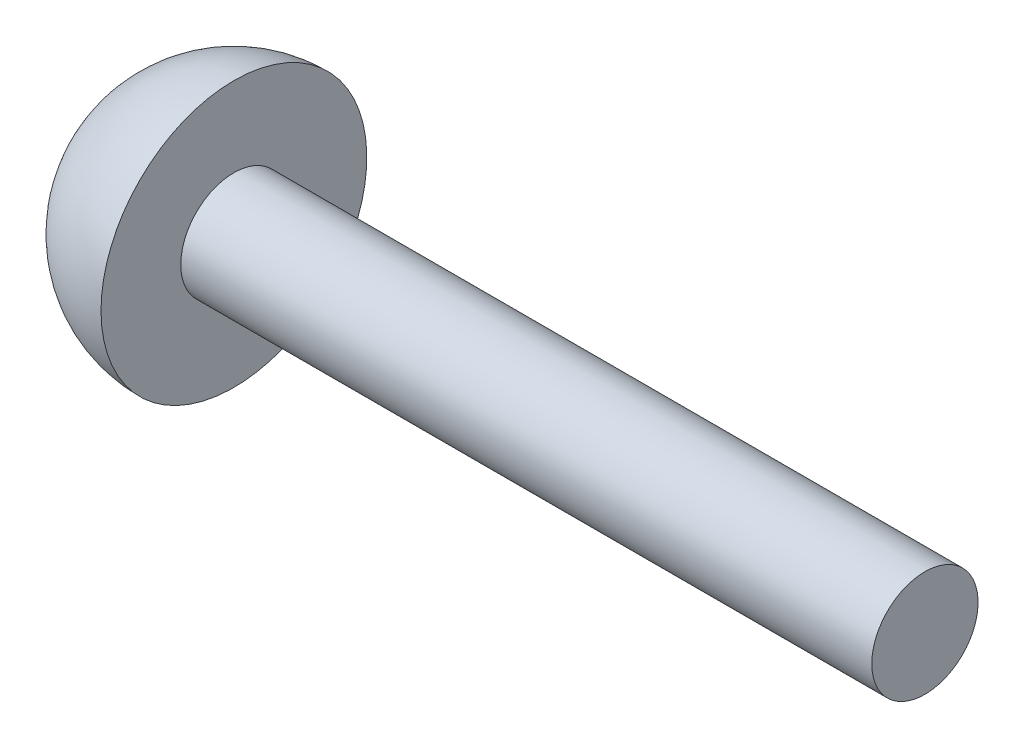
SolidWorks part; units mm, degrees
material "Mahogany"
ref_plane "Front" through (0, 0, 0) normal (0, 0, 1) x (1, 0, 0)
ref_plane "Top" through (0, 0, 0) normal (0, 1, 0) x (1, 0, 0)
ref_plane "Right" through (0, 0, 0) normal (1, 0, 0) x (0, 0, -1)
sketch "Sketch1" plane through (0, 0, 0) normal (0, 0, 1) x (1, 0, 0)
  line L0 (0, 0) -> (0, 2)
  line L1 (0, 2) -> (-26, 2)
  line L2 (-26, 2) -> (-26, 5)
  line L3 (-31, 0) -> (0, 0) construction
  line L4 (0, 0) -> (-31, 0)
  arc A0 (-26, 5) -> (-31, 0) centre (-26, 0) ccw
  dimension "D1" = 5
  dimension "D2" = 26
  dimension "D3" = 4
revolve "Revolve1" add sketch "Sketch1" angle 360 about L3
